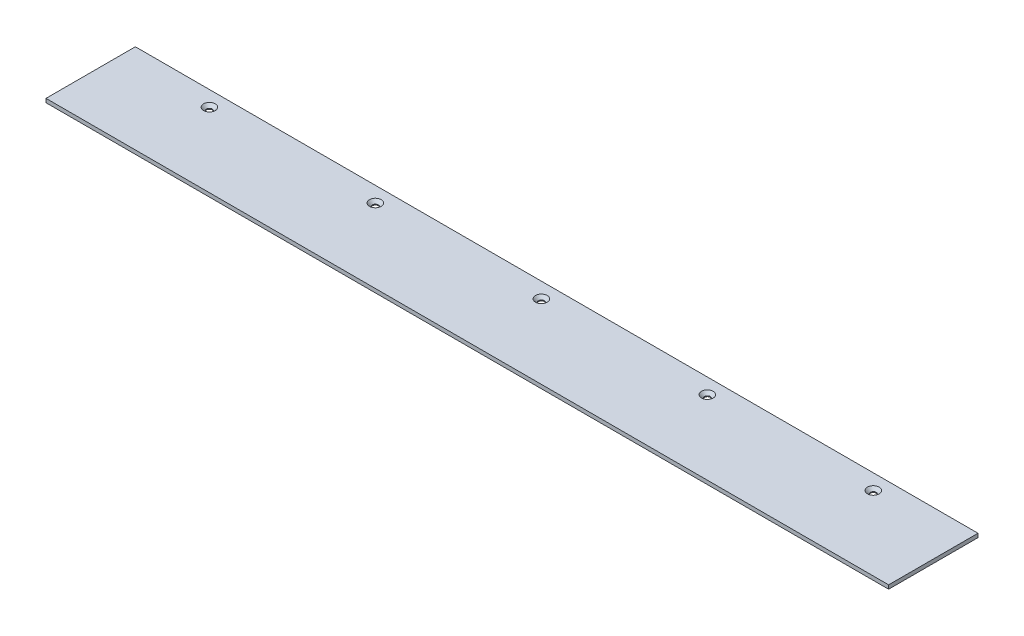
SolidWorks part; units mm, degrees
material "Aluminium"
ref_plane "Front Plane" through (0, 0, 0) normal (0, 0, 1) x (1, 0, 0)
ref_plane "Top Plane" through (0, 0, 0) normal (0, 1, 0) x (1, 0, 0)
ref_plane "Right Plane" through (0, 0, 0) normal (1, 0, 0) x (0, 0, -1)
sketch "Sketch1" plane through (0, 0, 0) normal (0, 1, 0) x (1, 0, 0)
  line L0 (0, 35) -> (0, -35) construction
  line L1 (-330, 35) -> (330, 35)
  line L2 (-330, 35) -> (-330, -35)
  line L3 (-330, -35) -> (330, -35)
  line L4 (330, 35) -> (330, -35)
  dimension "D1" = 70
  dimension "D2" = 660
extrude "Boss-Extrude1" add sketch "Sketch1" along normal blind 3
hole_wizard "CSK for M4 Hex Socket Countersunk Head Screw1" positions "Sketch3" profile "Sketch2" countersink size "M4" standard "DIN" end condition through all
sketch "Sketch3" plane through (0, 3, 0) normal (0, 1, 0) x (1, 0, 0)
  line L0 (-330, 35) -> (-330, -35) construction
  line L1 (-330, 23) -> (-260, 23) construction
  line L2 (330, 35) -> (-330, 35) construction
  point P0 (-260, 23)
  dimension "D1" = 70
  dimension "D2" = 12
sketch "Sketch2" plane through (-260, 3, -23) normal (1, 0, 0) x (0, 0, 1)
  line L0 (0, 0) -> (0, 3)
  line L1 (0, 3) -> (2.25, 3)
  line L2 (2.25, 3) -> (2.25, 2.34)
  line L3 (2.25, 2.34) -> (4.59, 0)
  line L5 (4.59, 0) -> (0, 0)
  line L6 (-2.25, 2.34) -> (-4.59, 0) construction
  line L11 (0, -6.35) -> (0, 107.95) construction
  dimension "Thru Hole Dia." = 4.5
  dimension "Thru Hole Depth" = 3
  dimension "Near C'Sink Dia." = 9.18
  dimension "Near C'Sink Angle" = 90
pattern_linear "LPattern1" count 5 spacing 130 along (1, 0, 0) of "CSK for M4 Hex Socket Countersunk Head Screw1"
